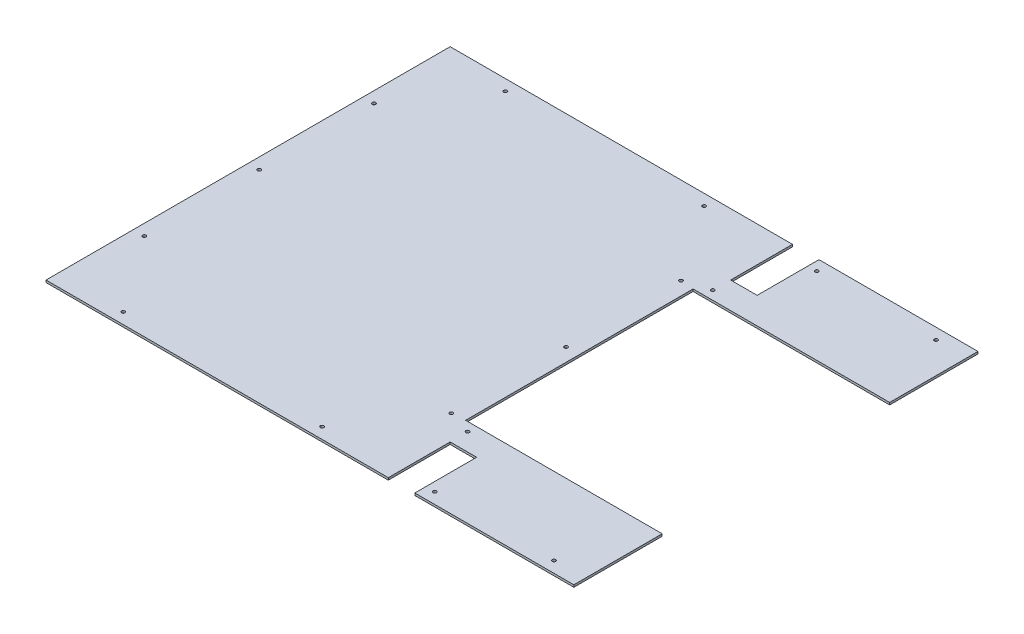
SolidWorks part; units mm, degrees
material "ABS PC"
ref_plane "Front Plane" through (0, 0, 0) normal (0, 0, 1) x (1, 0, 0)
ref_plane "Top Plane" through (0, 0, 0) normal (0, 1, 0) x (1, 0, 0)
ref_plane "Right Plane" through (0, 0, 0) normal (1, 0, 0) x (0, 0, -1)
sketch "Sketch1" plane through (0, 0, 0) normal (0, 1, 0) x (1, 0, 0)
  line L0 (476.25, 581.025) -> (758.825, 581.025)
  line L1 (0, 0) -> (447.675, 0)
  line L2 (0, 0) -> (0, 581.025)
  line L3 (0, 581.025) -> (476.25, 581.025)
  line L5 (758.825, 581.025) -> (758.825, 454.025)
  line L6 (758.825, 454.025) -> (476.25, 454.025)
  line L7 (447.675, 0) -> (758.825, 0)
  line L8 (758.825, 0) -> (758.825, 127)
  line L9 (758.825, 127) -> (476.25, 127)
  line L10 (476.25, 127) -> (476.25, 454.025)
  dimension "D1" = 476.25
  dimension "D2" = 581.025
  dimension "D3" = 282.575
  dimension "D4" = 282.575
  dimension "D5" = 127
  dimension "D6" = 127
  dimension "D7" = 282.575
extrude "Boss-Extrude1" add sketch "Sketch1" along normal blind 3.175
hole_wizard "#10 (0.1935) Diameter Hole2" positions "Sketch7" profile "Sketch6" hole size "#10" standard "ANSI Inch" end condition through all
sketch "Sketch7" plane through (0, 3.175, 0) normal (0, 1, 0) x (1, 0, 0)
  line L9 (0, 581.025) -> (0, 0) construction
  line L10 (758.825, 581.025) -> (0, 581.025) construction
  line L11 (0, 0) -> (758.825, 0) construction
  line L12 (15.875, 455.6125) -> (15.875, 125.4125) construction
  line L13 (457.2, 455.6125) -> (457.2, 125.4125) construction
  line L16 (381, 15.875) -> (95.25, 15.875) construction
  line L18 (381, 565.15) -> (95.25, 565.15) construction
  line L21 (476.25, 127) -> (476.25, 454.025) construction
  line L22 (476.25, 290.5125) -> (0, 290.5125) construction
  line L23 (0, 581.025) -> (0, 0) construction
  point P0 (15.875, 455.6125)
  point P14 (15.875, 125.4125)
  point P41 (15.875, 290.5125)
  point P46 (381, 565.15)
  point P48 (381, 15.875)
  point P50 (381, 565.15)
  point P70 (95.25, 565.15)
  point P72 (95.25, 15.875)
  point P74 (457.2, 125.4125)
  point P76 (457.2, 290.5125)
  point P78 (457.2, 455.6125)
  dimension "D1" = 381
  dimension "D2" = 15.875
  dimension "D3" = 165.1
  dimension "D4" = 165.1
  dimension "D5" = 15.875
  dimension "D6" = 381
  dimension "D7" = 15.875
  dimension "D8" = 165.1
  dimension "D9" = 165.1
  dimension "D10" = 19.05
  dimension "D11" = 95.25
  dimension "D12" = 95.25
  dimension "D13" = 0
  dimension "D14" = 0
sketch "Sketch6" plane through (15.875, 3.175, -455.6125) normal (1, 0, 0) x (0, 0, 1)
  line L0 (0, 0) -> (0, 3.175)
  line L1 (0, 3.175) -> (2.4574, 3.175)
  line L2 (2.4574, 3.175) -> (2.4574, 0)
  line L5 (2.4574, 0) -> (0, 0)
  line L11 (0, -6.35) -> (0, 107.95) construction
  dimension "Thru Hole Dia." = 4.9149
  dimension "Thru Hole Depth" = 3.175
sketch "Sketch8" plane through (0, 3.175, 0) normal (0, 1, 0) x (1, 0, 0)
  line L0 (0, 0) -> (758.825, 0) construction
  line L1 (492.125, 0) -> (530.225, 0)
  line L2 (492.125, 0) -> (492.125, 88.9)
  line L3 (492.125, 88.9) -> (530.225, 88.9)
  line L4 (530.225, 0) -> (530.225, 88.9)
  line L5 (758.825, 581.025) -> (0, 581.025) construction
  line L6 (492.125, 581.025) -> (530.225, 581.025)
  line L7 (492.125, 581.025) -> (492.125, 492.125)
  line L8 (492.125, 492.125) -> (530.225, 492.125)
  line L9 (530.225, 581.025) -> (530.225, 492.125)
  line L10 (758.825, 0) -> (758.825, 127) construction
  line L11 (758.825, 454.025) -> (758.825, 581.025) construction
  point P14 (492.125, 536.575)
  dimension "D1" = 266.7
  dimension "D2" = 38.1
  dimension "D3" = 88.9
  dimension "D4" = 266.7
  dimension "D5" = 38.1
  dimension "D6" = 88.9
extrude "Cut-Extrude1" cut sketch "Sketch8" against normal blind 3.175
hole_wizard "#10 (0.1935) Diameter Hole3" positions "Sketch9" profile "Sketch10" hole size "#10" standard "ANSI Inch" end condition through all
sketch "Sketch9" plane through (0, 3.175, 0) normal (0, 1, 0) x (1, 0, 0)
  line L0 (530.225, 0) -> (530.225, 88.9) construction
  line L2 (530.225, 0) -> (758.825, 0) construction
  line L3 (758.825, 0) -> (758.825, 127) construction
  line L4 (758.825, 454.025) -> (758.825, 581.025) construction
  line L5 (758.825, 581.025) -> (530.225, 581.025) construction
  line L7 (530.225, 492.125) -> (530.225, 581.025) construction
  line L8 (476.25, 454.025) -> (758.825, 454.025) construction
  line L9 (758.825, 127) -> (476.25, 127) construction
  line L10 (476.25, 127) -> (476.25, 454.025) construction
  point P0 (491.8075, 114.3)
  point P2 (542.925, 15.875)
  point P4 (714.375, 15.875)
  point P6 (491.8075, 466.725)
  point P8 (542.925, 565.15)
  point P10 (714.375, 565.15)
  dimension "D1" = 12.7
  dimension "D2" = 15.875
  dimension "D3" = 15.875
  dimension "D4" = 44.45
  dimension "D5" = 44.45
  dimension "D6" = 15.875
  dimension "D7" = 15.875
  dimension "D8" = 12.7
  dimension "D9" = 12.7
  dimension "D10" = 12.7
  dimension "D11" = 15.5575
  dimension "D12" = 15.5575
sketch "Sketch10" plane through (491.8075, 3.175, -114.3) normal (1, 0, 0) x (0, 0, 1)
  line L0 (0, 0) -> (0, 3.175)
  line L1 (0, 3.175) -> (2.4574, 3.175)
  line L2 (2.4574, 3.175) -> (2.4574, 0)
  line L5 (2.4574, 0) -> (0, 0)
  line L11 (0, -6.35) -> (0, 107.95) construction
  dimension "Thru Hole Dia." = 4.9149
  dimension "Thru Hole Depth" = 3.175
